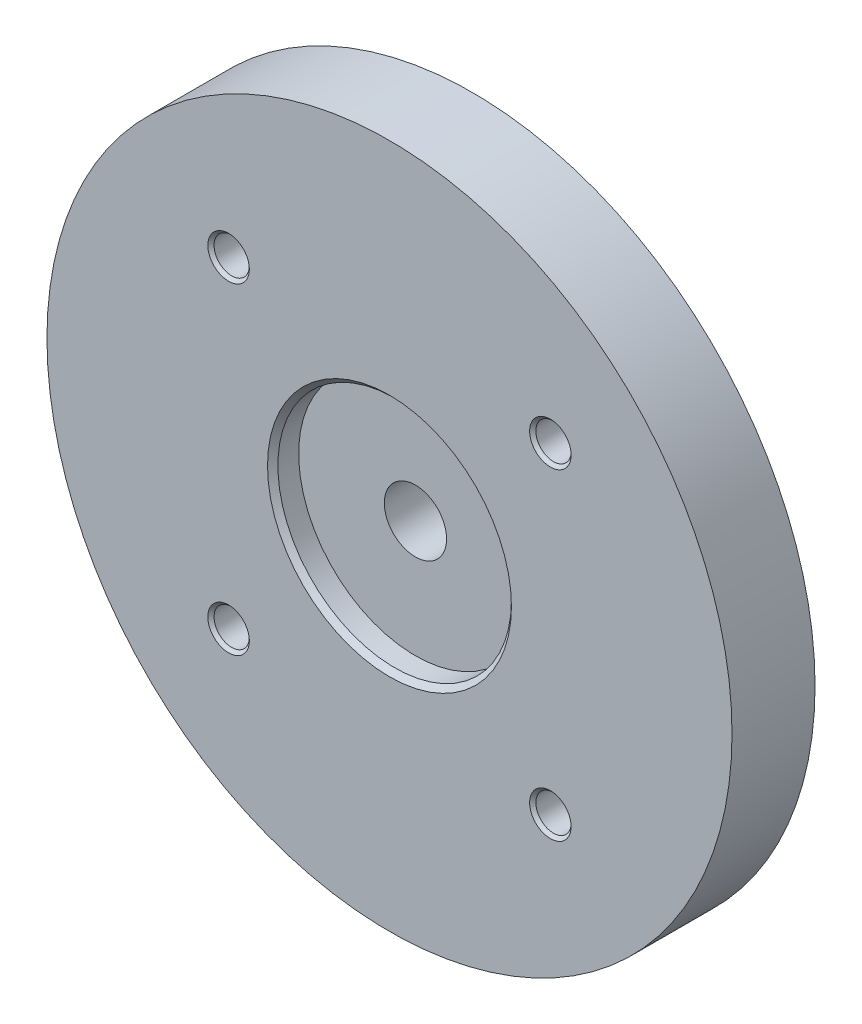
SolidWorks part; units mm, degrees
ref_plane "Front Plane" through (0, 0, 0) normal (0, 0, 1) x (1, 0, 0)
ref_plane "Top Plane" through (0, 0, 0) normal (0, 1, 0) x (1, 0, 0)
ref_plane "Right Plane" through (0, 0, 0) normal (1, 0, 0) x (0, 0, -1)
sketch "Sketch2" plane through (0, 0, 0) normal (0, 0, 1) x (1, 0, 0)
  circle A0 centre (0, 0) radius 33
  dimension "D1" = 66
extrude "Boss-Extrude1" add sketch "Sketch2" along normal blind 8
sketch "Sketch6" plane through (0, 0, 0) normal (0, 0, -1) x (-1, 0, 0)
  circle A0 centre (0, 0) radius 10
  dimension "D1" = 20
extrude "Boss-Extrude2" add sketch "Sketch6" along normal blind 2
sketch "Sketch3" plane through (0, 0, 8) normal (0, 0, 1) x (1, 0, 0)
  line L0 (0, -15.5) -> (0, 15.5) construction
  line L1 (15.5, 15.5) -> (-15.5, 15.5) construction
  line L2 (15.5, -15.5) -> (-15.5, -15.5) construction
  circle A0 centre (-15.5, 15.5) radius 1.7
  circle A1 centre (15.5, 15.5) radius 1.7
  circle A2 centre (15.5, -15.5) radius 1.7
  circle A3 centre (-15.5, -15.5) radius 1.7
  circle A4 centre (0, 0) radius 3
  point P12 (0, 0)
  point P16 (0, 15.5)
  point P19 (0, -15.5)
  dimension "D1" = 3.4
  dimension "D2" = 3.4
  dimension "D3" = 3.4
  dimension "D4" = 3.4
  dimension "D8" = 6
  dimension "D5" = 31
  dimension "D6" = 31
  dimension "D7" = 31
extrude "Cut-Extrude1" cut sketch "Sketch3" against normal through all both and the other way through all
sketch "Sketch4" plane through (0, 0, 0) normal (0, 0, -1) x (-1, 0, 0)
  circle A0 centre (-15.5, 15.5) radius 2.8
  circle A1 centre (15.5, 15.5) radius 2.8
  circle A2 centre (15.5, -15.5) radius 2.8
  circle A3 centre (-15.5, -15.5) radius 2.8
  dimension "D1" = 5.6
  dimension "D2" = 5.6
  dimension "D3" = 5.6
  dimension "D4" = 5.6
extrude "Cut-Extrude2" cut sketch "Sketch4" against normal blind 2 and the other way through all
sketch "Sketch5" plane through (0, 0, 0) normal (0, 0, -1) x (-1, 0, 0)
  circle A0 centre (0, 29.5) radius 2.1
  circle A1 centre (29.5, 0) radius 2.1
  circle A2 centre (0, -29.5) radius 2.1
  circle A3 centre (-29.5, 0) radius 2.1
  point P19 (0, 0)
  dimension "D1" = 4.2
  dimension "D2" = 29.5
  dimension "D3" = 4
extrude "Cut-Extrude3" cut sketch "Sketch5" against normal blind 6
fillet "Fillet1" radius 1 1 edges at (-10, 0, 0)
sketch "Sketch7" plane through (0, 0, 8) normal (0, 0, 1) x (1, 0, 0)
  circle A0 centre (0, 0) radius 11.25
  dimension "D1" = 22.5
extrude "Cut-Extrude4" cut sketch "Sketch7" against normal blind 2.5
chamfer "Chamfer1" distance 0.5 angle 45 1 edges at (11.25, 0, 8)
chamfer "Chamfer2" distance 0.3 angle 45 4 edges at (-13.8, -15.5, 8) (17.2, -15.5, 8) (17.2, 15.5, 8) (-13.8, 15.5, 8)
equation "\"N_pins\"= 26"
equation "\"N_lobes\"= \"N_pins\" - 1"
equation "\"R_pc\"= 25"
equation "\"D_pin\"= 3"
equation "\"R_pin\"= \"D_pin\" / 2"
equation "\"ecc\"= 0.72"
equation "\"t_disc\"= 7"
equation "\"N_out\"= 8"
equation "\"D_outc\"=22"
equation "\"D_roller\"= 5"
equation "\"D_outhole\"= \"D_roller\" + 2 * \"ecc\""
equation "\"D_cam_OD\"= 21"
equation "\"D_cam_ID\"= 10"
equation "\"clr_bore\"= 1"
equation "\"D_bore\"= 2 * \"R_pc\" + \"clr_bore\""
equation "\"t_wall\"= 7.5"
equation "\"D_housing\"= \"D_bore\" + 2 * \"t_wall\""
equation "\"D1@Sketch2\"=\"D_housing\""
